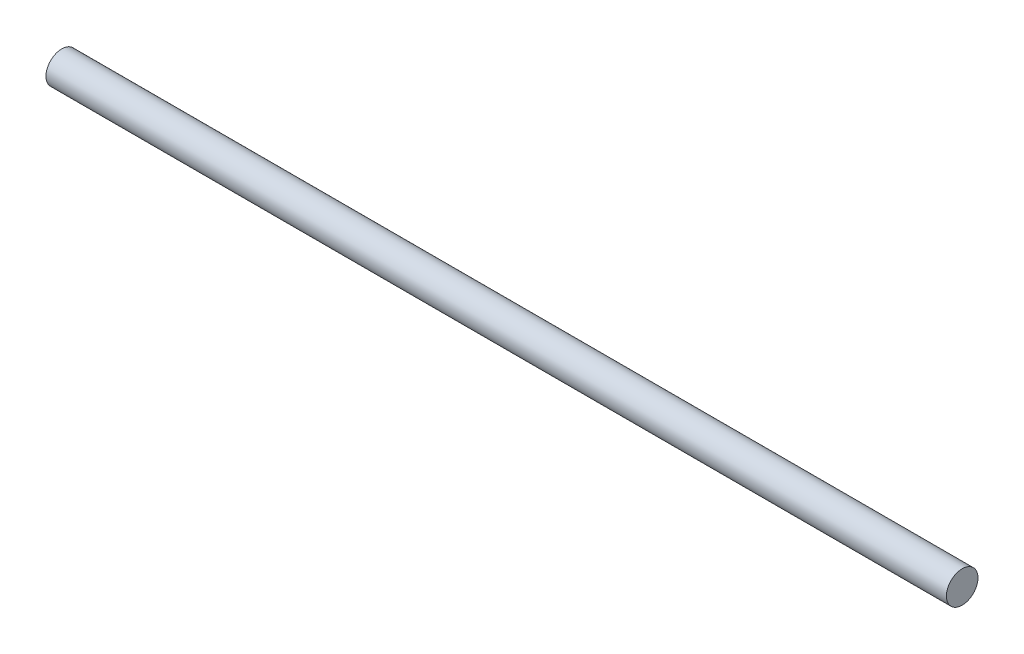
SolidWorks part; units mm, degrees
material "Cast Carbon Steel"
ref_plane "Front Plane" through (0, 0, 0) normal (0, 0, 1) x (1, 0, 0)
ref_plane "Top Plane" through (0, 0, 0) normal (0, 1, 0) x (1, 0, 0)
ref_plane "Right Plane" through (0, 0, 0) normal (1, 0, 0) x (0, 0, -1)
sketch "Sketch1" plane through (0, 0, 0) normal (1, 0, 0) x (0, 0, -1)
  circle A0 centre (0, 0) radius 12.7
  dimension "D1" = 25.4
extrude "Boss-Extrude1" add sketch "Sketch1" along normal blind 723.9
